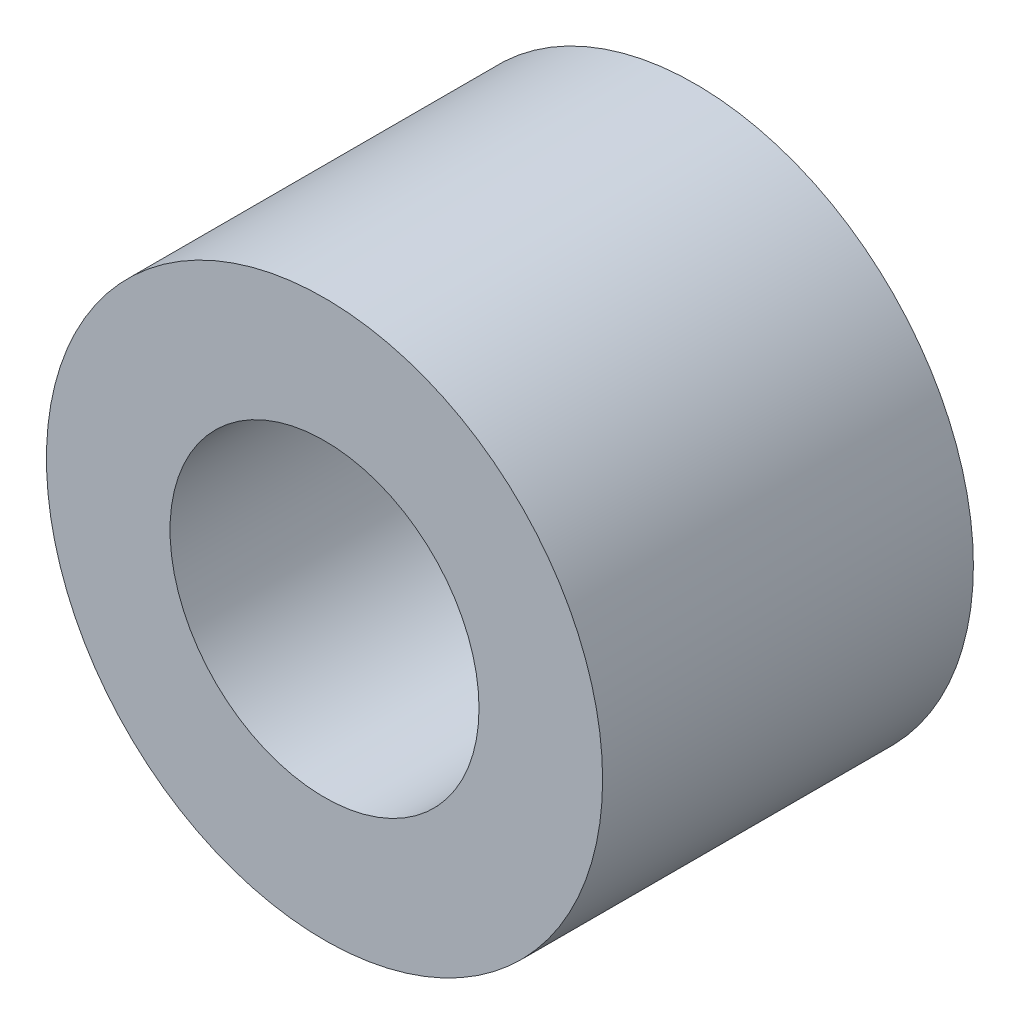
SolidWorks part; units mm, degrees
material "Copper"
ref_plane "Front Plane" through (0, 0, 0) normal (0, 0, 1) x (1, 0, 0)
ref_plane "Top Plane" through (0, 0, 0) normal (0, 1, 0) x (1, 0, 0)
ref_plane "Right Plane" through (0, 0, 0) normal (1, 0, 0) x (0, 0, -1)
sketch "Sketch1" plane through (0, 0, 0) normal (0, 0, 1) x (1, 0, 0)
  circle A0 centre (0, 0) radius 2.5
  circle A1 centre (0, 0) radius 4.5
  dimension "D1" = 5
  dimension "D2" = 9
extrude "Boss-Extrude1" add sketch "Sketch1" along normal blind 6
